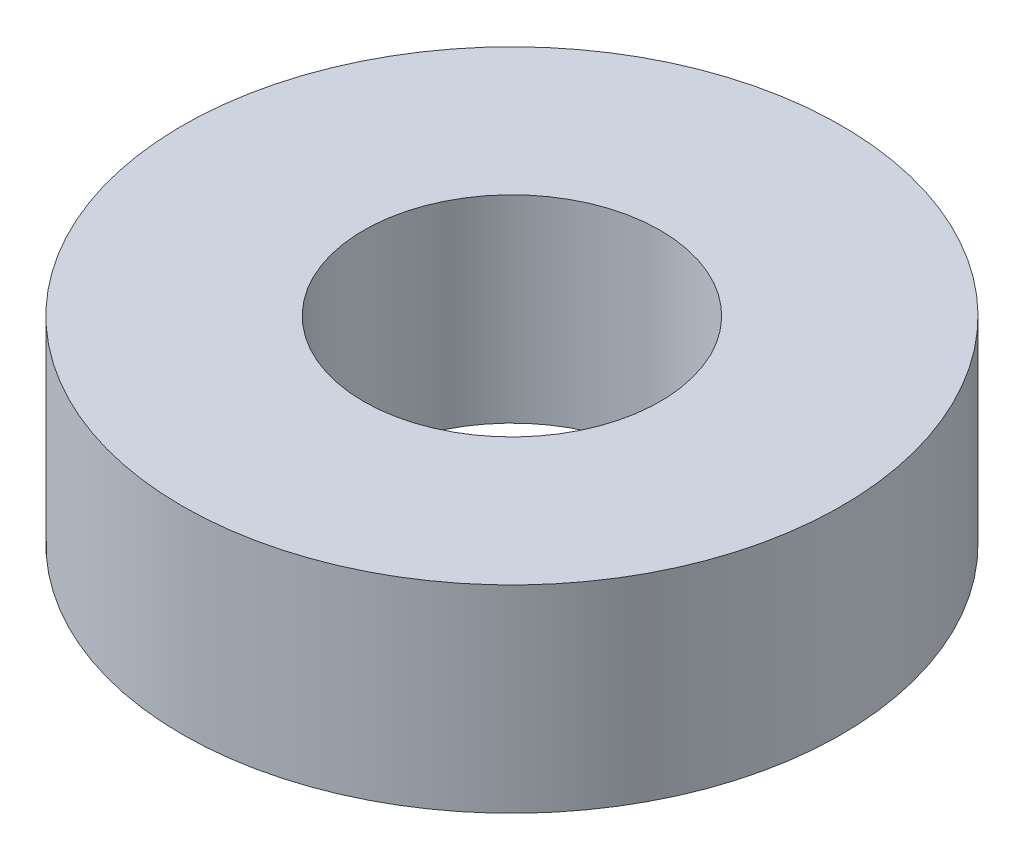
SolidWorks part; units mm, degrees
ref_plane "Plan de face" through (0, 0, 0) normal (0, 0, 1) x (1, 0, 0)
ref_plane "Plan de dessus" through (0, 0, 0) normal (0, 1, 0) x (1, 0, 0)
ref_plane "Plan de droite" through (0, 0, 0) normal (1, 0, 0) x (0, 0, -1)
sketch "Esquisse1" plane through (0, 0, 0) normal (0, 1, 0) x (1, 0, 0)
  circle A0 centre (0, 0) radius 10
  circle A1 centre (0, 0) radius 4.5
  dimension "D1" = 9
  dimension "D2" = 20
extrude "Boss.-Extru.1" add sketch "Esquisse1" along normal blind 6
